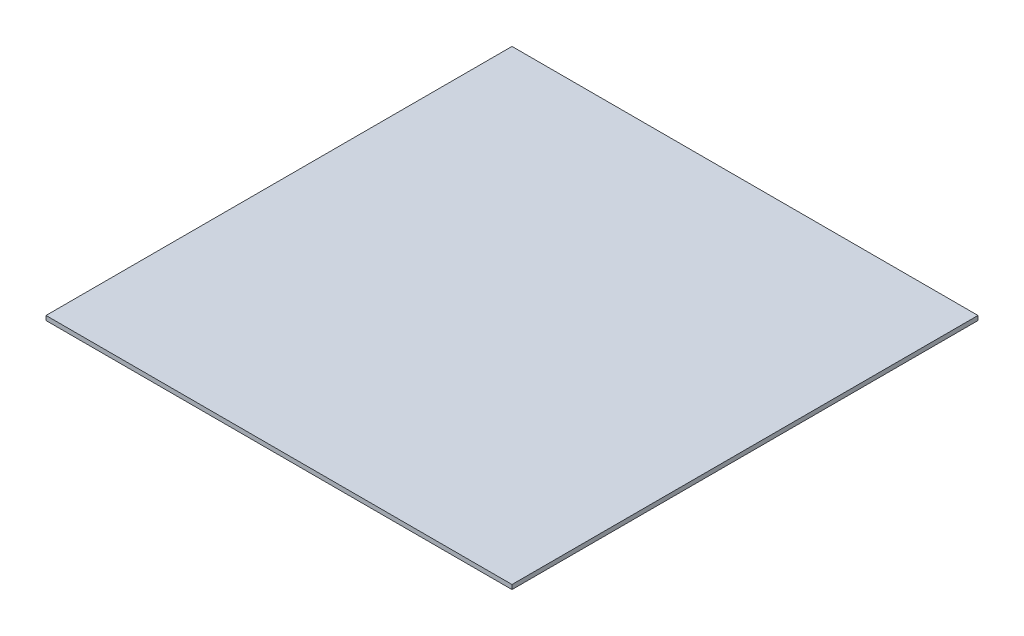
SolidWorks part; units mm, degrees
ref_plane "Front Plane" through (0, 0, 0) normal (0, 0, 1) x (1, 0, 0)
ref_plane "Top Plane" through (0, 0, 0) normal (0, 1, 0) x (1, 0, 0)
ref_plane "Right Plane" through (0, 0, 0) normal (1, 0, 0) x (0, 0, -1)
sketch "Sketch1" plane through (0, 0, 0) normal (0, 1, 0) x (1, 0, 0)
  line L1 (-200, -200) -> (200, -200)
  line L2 (-200, -200) -> (-200, 200)
  line L3 (-200, 200) -> (200, 200)
  line L4 (200, -200) -> (200, 200)
  line L5 (-200, -200) -> (200, 200) construction
  line L6 (-200, 200) -> (200, -200) construction
  point P0 (0, 0)
  dimension "D1" = 400
extrude "Boss-Extrude1" add sketch "Sketch1" along normal blind 3.8
